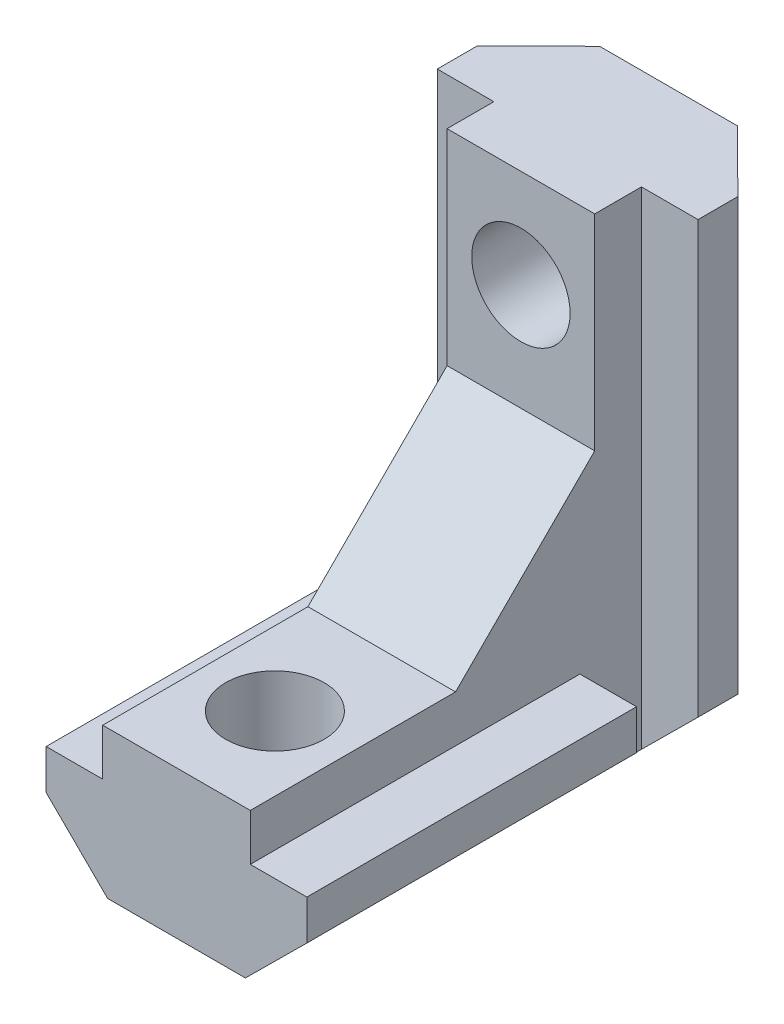
SolidWorks part; units mm, degrees
ref_plane "Front (XY)" through (0, 0, 0) normal (0, 0, 1) x (1, 0, 0)
ref_plane "Top (XZ)" through (0, 0, 0) normal (0, 1, 0) x (1, 0, 0)
ref_plane "Right (YZ)" through (0, 0, 0) normal (1, 0, 0) x (0, 0, -1)
sketch "Sketch1" plane through (0, 0, 0) normal (0, 0, 1) x (1, 0, 0)
  line L0 (0, 0) -> (0, 6) construction
  line L11 (-3, 6) -> (3, 6)
  line L12 (-3, 6) -> (-3, 4.1)
  line L13 (3, 6) -> (3, 4.1)
  line L14 (-3, 4.1) -> (-5.3, 4.1)
  line L15 (3, 4.1) -> (5.3, 4.1)
  line L16 (-5.3, 4.1) -> (-5.3, 2.48)
  line L17 (5.3, 4.1) -> (5.3, 2.48)
  line L18 (-2.8, 0) -> (2.8, 0)
  line L19 (-2.8, 0) -> (-5.3, 2.48)
  line L20 (2.8, 0) -> (5.3, 2.48)
  point P4 (0, 6)
  point P14 (0, 0)
  dimension "D1" = 6
  dimension "D2" = 6
  dimension "D3" = 2.3
  dimension "D4" = 4.1
  dimension "D5" = 3.5214
  dimension "D6" = 1.62
extrude "Boss-Extrude1" add sketch "Sketch1" along normal blind 20
sketch "Sketch2" plane through (-0.0097, 0, -0.067) normal (0, 1, 0) x (-1, 0, 0)
  line L0 (-0.0097, 0.067) -> (-0.0097, 6.067) construction
  line L1 (-3.0097, 6.067) -> (2.9903, 6.067)
  line L2 (-3.0097, 6.067) -> (-3.0097, 4.167)
  line L3 (2.9903, 6.067) -> (2.9903, 4.167)
  line L4 (-3.0097, 4.167) -> (-5.3097, 4.167)
  line L5 (2.9903, 4.167) -> (5.2903, 4.167)
  line L6 (-5.3097, 4.167) -> (-5.3097, 2.547)
  line L7 (5.2903, 4.167) -> (5.2903, 2.547)
  line L8 (-2.8097, 0.067) -> (2.7903, 0.067)
  line L9 (-2.8097, 0.067) -> (-5.3097, 2.547)
  line L10 (2.7903, 0.067) -> (5.2903, 2.547)
  point P4 (-0.0097, 6.067)
  point P13 (-0.0097, 0.067)
  dimension "D1" = 6
  dimension "D2" = 6
  dimension "D3" = 2.3
  dimension "D4" = 1.62
  dimension "D5" = 3.5214
  dimension "D6" = 1.9
extrude "Boss-Extrude2" add sketch "Sketch2" along normal blind 20
sketch "Sketch3" plane through (0, 0, 0) normal (0, 1, 0) x (1, 0, 0)
  line L0 (-2.8, 0) -> (-5.3, -2.48) construction
  line L1 (-2.8, 0) -> (-5.3, -2.48)
  line L2 (5.3, -2.48) -> (5.3, 0) construction
  line L3 (5.3, -2.48) -> (5.3, 0)
  line L4 (2.8, 0) -> (5.3, 0) construction
  line L5 (2.8, 0) -> (5.3, 0)
  line L6 (5.3, -2.48) -> (2.8, 0) construction
  line L7 (5.3, -2.48) -> (2.8, 0)
  line L8 (-5.3, -2.48) -> (-5.3, 0) construction
  line L9 (-5.3, -2.48) -> (-5.3, 0)
  line L10 (-5.3, 0) -> (-2.8, 0) construction
  line L11 (-5.3, 0) -> (-2.8, 0)
extrude "Cut-Extrude3" cut sketch "Sketch3" against normal through all and the other way through all
sketch "Sketch4" plane through (0, 0, 0) normal (0, 0, 1) x (1, 0, 0)
  line L1 (2.8, 0) -> (3, 0) construction
  line L2 (3, 0) -> (5.3, 0) construction
  line L3 (5.3, 2.48) -> (5.3, 0) construction
  line L5 (-5.3, 2.48) -> (-5.3, 0) construction
  line L6 (-3, 0) -> (-2.8, 0) construction
  line L7 (-5.3, 0) -> (-3, 0) construction
  line L10 (2.8, 0) -> (3, 0)
  line L11 (3, 0) -> (5.3, 0)
  line L12 (5.3, 2.48) -> (5.3, 0)
  line L13 (5.3, 2.48) -> (2.8, 0)
  line L14 (-5.3, 2.48) -> (-5.3, 0)
  line L15 (-3, 0) -> (-2.8, 0)
  line L16 (-5.3, 0) -> (-3, 0)
  line L18 (-5.3, 2.48) -> (-2.8, 0) construction
  line L19 (-5.3, 2.48) -> (-2.8, 0)
extrude "Cut-Extrude4" cut sketch "Sketch4" along normal through all
sketch "Sketch5" plane through (0, 0, 0) normal (1, 0, 0) x (0, 0, -1)
  line L0 (-20, 6) -> (-6, 6) construction
  line L1 (-6, 20) -> (-6, 6) construction
  line L2 (-11.6569, 6) -> (-6, 6)
  line L3 (-6, 11.6569) -> (-6, 6)
  line L4 (-6, 11.6569) -> (-11.6569, 6)
  dimension "D1" = 8
  dimension "D2" = 45
extrude "Boss-Extrude3" add sketch "Sketch5" along normal mid plane 6
sketch "Sketch10" plane through (0, 0, 0) normal (0, 1, 0) x (1, 0, 0)
  line L0 (-5.3, -4.1) -> (-3, -4.1) construction
  line L1 (-5.3, -4.1) -> (-3, -4.1)
  line L2 (-3, -20) -> (-3, -4.1) construction
  line L3 (-3, -6) -> (-3, -4.1)
  line L7 (3, -6) -> (3, -4.1) construction
  line L9 (3, -4.1) -> (5.3, -4.1) construction
  line L10 (3, -6) -> (3, -4.1)
  line L12 (3, -4.1) -> (5.3, -4.1)
  line L15 (-5.3, -4.1) -> (-5.3, -6.6)
  line L16 (-5.3, -20) -> (-5.3, -4.1) construction
  line L17 (-5.3, -6.6) -> (-3, -6.6)
  line L18 (-3, -6.6) -> (-3, -6)
  line L19 (5.3, -4.1) -> (5.3, -6.6)
  line L20 (5.3, -20) -> (5.3, -4.1) construction
  line L21 (5.3, -6.6) -> (3, -6.6)
  line L22 (3, -6.6) -> (3, -6)
  dimension "D1" = 2.5
  dimension "D2" = 2.5
extrude "Cut-Extrude5" cut sketch "Sketch10" along normal through all
sketch "Sketch11" plane through (0, 0, 6) normal (0, 0, 1) x (1, 0, 0)
  line L0 (-3, 20) -> (3, 20) construction
  circle A0 centre (0, 16) radius 2
  dimension "D1" = 4
  dimension "D2" = 16
  dimension "D3" = 4
extrude "Cut-Extrude6" cut sketch "Sketch11" against normal through all
sketch "Sketch12" plane through (0, 6, 0) normal (0, 1, 0) x (1, 0, 0)
  line L0 (3, -20) -> (-3, -20) construction
  circle A0 centre (0, -16) radius 2
  dimension "D1" = 4
  dimension "D2" = 16
  dimension "D3" = 4
extrude "Cut-Extrude7" cut sketch "Sketch12" against normal blind 10
